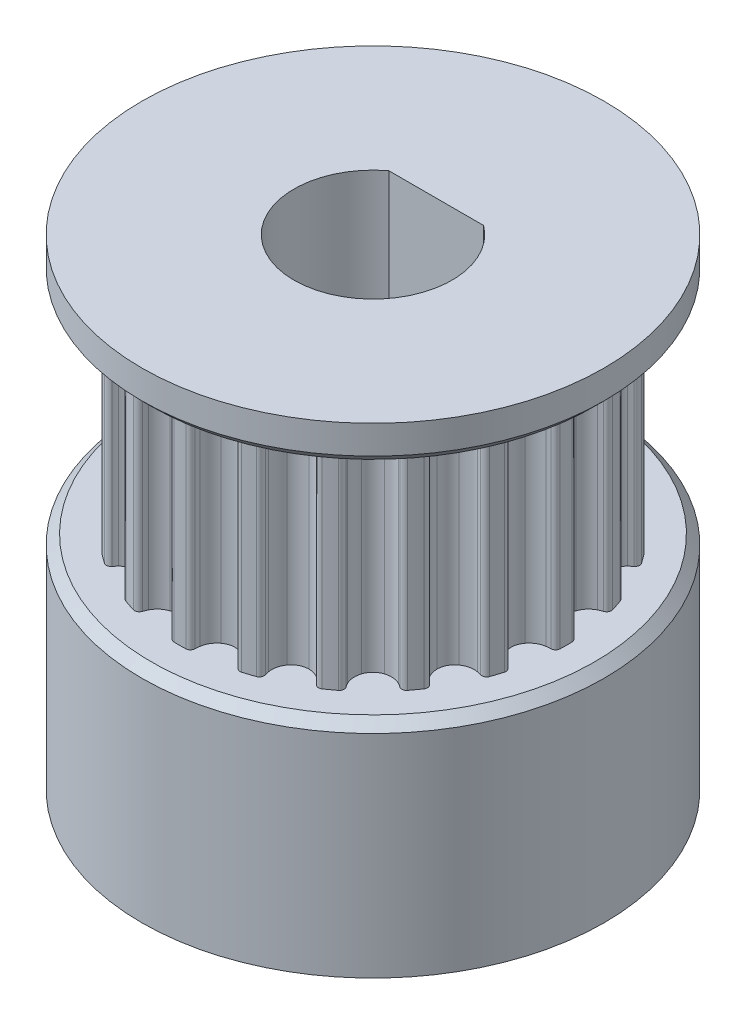
SolidWorks part; units mm, degrees
ref_plane "Front Plane" through (0, 0, 0) normal (0, 0, 1) x (1, 0, 0)
ref_plane "Top Plane" through (0, 0, 0) normal (0, 1, 0) x (1, 0, 0)
ref_plane "Right Plane" through (0, 0, 0) normal (1, 0, 0) x (0, 0, -1)
sketch "Sketch1" plane through (0, 0, 0) normal (0, 1, 0) x (1, 0, 0)
  line L0 (0, 0) -> (0, 6.3662) construction
  line L1 (0, 0) -> (0.9959, 6.2878) construction
  line L2 (0, 0) -> (1.3887, 6.2129) construction
  circle A0 centre (0, 0) radius 6.3662 construction
  circle A1 centre (0, 0) radius 5.3622 construction
  circle A2 centre (0, 0) radius 6.1122 construction
  arc A3 (0.8388, 5.2962) -> (0.5917, 5.401) centre (0.9257, 5.8443) cw
  arc A4 (0.3445, 5.8158) -> (0.3333, 5.9601) centre (1.3333, 5.965) cw
  circle A5 centre (0, 0) radius 5.9622 construction
  arc A6 (-0.188, 6.1093) -> (0.188, 6.1093) centre (0, 0) cw
  arc A7 (0.188, 6.1093) -> (0.3333, 5.9601) centre (0.1833, 5.9594) cw
  arc A8 (0.3445, 5.8158) -> (0.5917, 5.401) centre (0.9759, 5.9111) ccw
  arc A9 (-0.8388, 5.2962) -> (-0.5917, 5.401) centre (-0.9257, 5.8443) ccw
  arc A10 (-0.3445, 5.8158) -> (-0.5917, 5.401) centre (-0.9759, 5.9111) cw
  arc A11 (-0.3445, 5.8158) -> (-0.3333, 5.9601) centre (-1.3333, 5.965) ccw
  arc A12 (-0.188, 6.1093) -> (-0.3333, 5.9601) centre (-0.1833, 5.9594) ccw
  arc A13 (-0.8388, 5.2962) -> (0.8388, 5.2962) centre (0, 0) cw
  point P13 (1.3333, 5.965)
  point P16 (0, 6.1122)
  dimension "D1" = 12.7324
  dimension "D6" = 0.555
  dimension "D7" = 1
  dimension "D9" = 0.15
  dimension "D2" = 9
  dimension "D3" = 3.6
  dimension "D4" = 1.004
  dimension "D5" = 0.75
  dimension "D8" = 0.15
extrude "Boss-Extrude1" add sketch "Sketch1" along normal blind 7 contours A9 A13 A3 A8 A4 A7 A6 A12 A11 A10
sketch "Sketch2" plane through (0, 0, 0) normal (0, -1, 0) x (1, 0, 0)
  circle A0 centre (0, 0) radius 5.3622
  arc A2 (-0.8388, -5.2962) -> (0.8388, -5.2962) centre (0, 0) ccw construction
  arc A5 (-0.8388, -5.2962) -> (0.8388, -5.2962) centre (0, 0) ccw
  arc M3 (-0.8388, -5.2962) -> (-0.5917, -5.401) centre (-0.9257, -5.8443) cw
  arc M4 (-0.5917, -5.401) -> (-0.3445, -5.8158) centre (-0.9759, -5.9111) cw
  arc M5 (-0.3445, -5.8158) -> (-0.3333, -5.9601) centre (-1.3333, -5.965) cw
  arc M6 (-0.3333, -5.9601) -> (-0.188, -6.1093) centre (-0.1833, -5.9594) ccw
  arc M7 (-0.188, -6.1093) -> (0.188, -6.1093) centre (0, 0) ccw
  arc M8 (0.188, -6.1093) -> (0.3333, -5.9601) centre (0.1833, -5.9594) ccw
  arc M9 (0.3333, -5.9601) -> (0.3445, -5.8158) centre (1.3333, -5.965) cw
  arc M10 (0.3445, -5.8158) -> (0.5917, -5.401) centre (0.9759, -5.9111) cw
  arc M11 (0.5917, -5.401) -> (0.8388, -5.2962) centre (0.9257, -5.8443) cw
  arc M12 (0.8388, -5.2962) -> (-0.8388, -5.2962) centre (0, 0) cw
extrude "Boss-Extrude2" add sketch "Sketch2" against normal blind 7 contours A0 M3 M12 M11 M10 M9 M8 M7 M6 M5 M4
pattern_circular "CirPattern3" count 20 over 360 about axis through (0, 0, 0) along (0, 1, 0) of "Boss-Extrude1"
sketch "Sketch3" plane through (0, 7, 0) normal (0, 1, 0) x (1, 0, 0)
  circle A0 centre (0, 0) radius 7.3122
  arc A3 (0.2249, 7.3087) -> (-0.2249, 7.3087) centre (0, 0) ccw
  arc A4 (0.2249, 7.3087) -> (-0.2249, 7.3087) centre (0, 0) ccw
  dimension "D1" = 1.2
extrude "Boss-Extrude3" add sketch "Sketch3" along normal blind 1.2 contours A0
sketch "Sketch4" plane through (0, 0, 0) normal (0, -1, 0) x (1, 0, 0)
  circle A0 centre (0, 0) radius 7.3122 construction
  circle A1 centre (0, 0) radius 7.3122
extrude "Boss-Extrude4" add sketch "Sketch4" along normal blind 7
sketch "Sketch5" plane through (0, 8.2, 0) normal (0, 1, 0) x (1, 0, 0)
  line L0 (-1.5, 2) -> (1.5, 2)
  circle A0 centre (0, 0) radius 2.5
  dimension "D1" = 5
  dimension "D2" = 2
extrude "Cut-Extrude1" cut sketch "Sketch5" against normal through all contours L0 A0
chamfer "Chamfer1" distance 0.3 angle 45 2 edges at (0, 7, 7.3122) (0, 0, -7.3122)
equation "\"TeethNumber\"= 20"
equation "\"Pitch\"= 2"
equation "\"PullyDiameter\"= \"TeethNumber\" * \"Pitch\" / PI"
equation "\"ToothAngle\"= ( 360 / \"TeethNumber\" ) * 1deg"
equation "\"TransOffsetAngle\"= \"ToothAngle\" * 0.2' "
equation "\"ShoulderRadius\"= 0.15"
equation "\"RootRadius\"= 0.555"
equation "\"TransRadius\"= 1"
equation "\"ToothHeight\"= 0.75"
equation "\"PLD\"= 0.254"
equation "\"D1@Sketch1\"=\"PullyDiameter\""
equation "\"D2@Sketch1\"=\"ToothAngle\"/2"
equation "\"D3@Sketch1\"=\"TransOffsetAngle\""
equation "\"D4@Sketch1\"=\"PLD\"+\"ToothHeight\""
equation "\"D5@Sketch1\"=\"ToothHeight\""
equation "\"D6@Sketch1\" = \"RootRadius\""
equation "\"D7@Sketch1\"=\"TransRadius\""
equation "\"D9@Sketch1\"=\"ShoulderRadius\""
